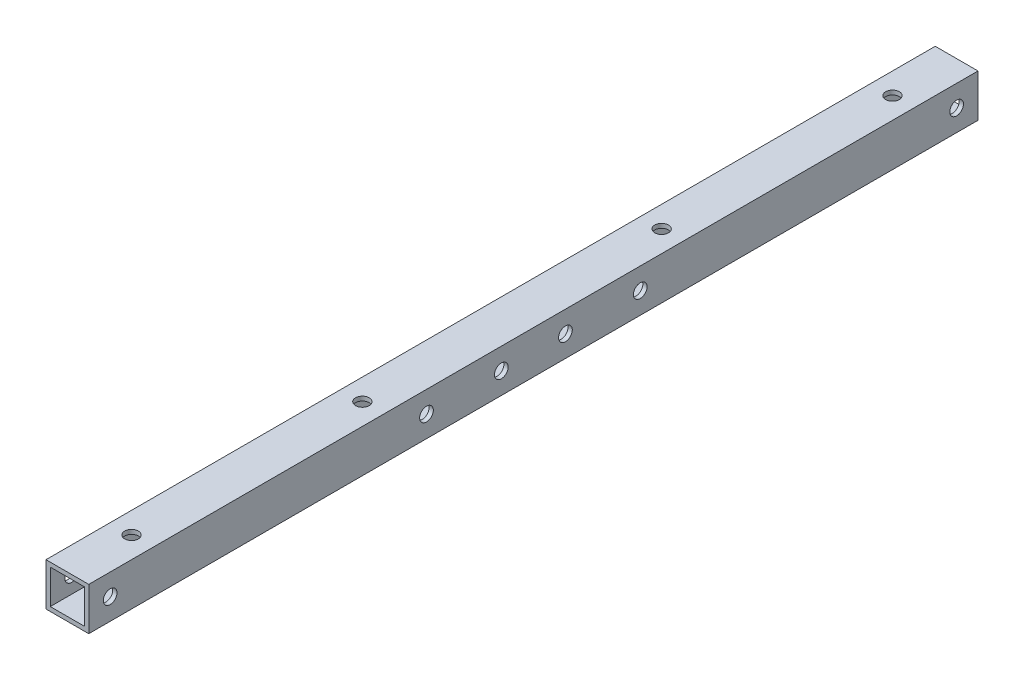
SolidWorks part; units mm, degrees
ref_plane "正面" through (0, 0, 0) normal (0, 0, 1) x (1, 0, 0)
ref_plane "平面" through (0, 0, 0) normal (0, 1, 0) x (1, 0, 0)
ref_plane "右側面" through (0, 0, 0) normal (1, 0, 0) x (0, 0, -1)
sketch "ｽｹｯﾁ1" plane through (0, 0, 0) normal (0, 0, 1) x (1, 0, 0)
  line L0 (-4, 4) -> (-4, -4)
  line L1 (-5, 5) -> (5, 5)
  line L2 (-5, 5) -> (-5, -5)
  line L3 (-5, -5) -> (5, -5)
  line L4 (5, 5) -> (5, -5)
  line L5 (-5, 5) -> (5, -5) construction
  line L6 (-5, -5) -> (5, 5) construction
  line L7 (-4, -4) -> (4, -4)
  line L8 (4, 4) -> (4, -4)
  line L9 (-4, 4) -> (4, 4)
  point P0 (0, 0)
  dimension "D1" = 10
  dimension "D2" = 10
  dimension "D3" = 1
extrude "ﾎﾞｽ - 押し出し1" add sketch "ｽｹｯﾁ1" along normal blind 208
sketch "ｽｹｯﾁ2" plane through (5, 0, 0) normal (1, 0, 0) x (0, 0, -1)
  line L0 (5.5, 0) -> (-5.5, 0) construction
  line L1 (-208, -5) -> (-208, 5) construction
  line L2 (0, 5.5) -> (0, -5.5) construction
  circle A0 centre (-203, 0) radius 1.6
  circle A1 centre (-111.5, 0) radius 1.6
  circle A2 centre (-96.5, 0) radius 1.6
  circle A3 centre (-5, 0) radius 1.6
  dimension "D1" = 3.2
  dimension "D2" = 3.2
  dimension "D3" = 3.2
  dimension "D4" = 3.2
  dimension "D5" = 5
  dimension "D6" = 5
  dimension "D7" = 15
  dimension "D8" = 96.5
extrude "ｶｯﾄ - 押し出し1" cut sketch "ｽｹｯﾁ2" against normal through all
sketch "ｽｹｯﾁ3" plane through (0, 5, 0) normal (0, 1, 0) x (1, 0, 0)
  line L0 (0, -5.5) -> (0, 5.5) construction
  line L1 (5, -208) -> (-5, -208) construction
  line L2 (-5.5, 0) -> (5.5, 0) construction
  circle A0 centre (0, -193) radius 1.6
  circle A1 centre (0, -15) radius 1.6
  dimension "D1" = 3.2
  dimension "D2" = 15
  dimension "D3" = 3.2
  dimension "D4" = 15
extrude "ｶｯﾄ - 押し出し2" cut sketch "ｽｹｯﾁ3" against normal through all
sketch "ｽｹｯﾁ4" plane through (5, 0, 0) normal (1, 0, 0) x (0, 0, -1)
  line L0 (5.5, 0) -> (-5.5, 0) construction
  line L1 (-208, -5) -> (-208, 5) construction
  circle A0 centre (-129, 0) radius 1.6
  circle A1 centre (-79, 0) radius 1.6
  dimension "D1" = 3.2
  dimension "D2" = 3.2
  dimension "D3" = 50
  dimension "D4" = 79
extrude "ｶｯﾄ - 押し出し3" cut sketch "ｽｹｯﾁ4" against normal through all
sketch "ｽｹｯﾁ5" plane through (0, 5, 0) normal (0, 1, 0) x (1, 0, 0)
  line L0 (0, -5.5) -> (0, 5.5) construction
  line L1 (5, -208) -> (-5, -208) construction
  line L2 (-5.5, 0) -> (5.5, 0) construction
  circle A0 centre (0, -139) radius 1.6
  circle A1 centre (0, -69) radius 1.6
  dimension "D1" = 3.2
  dimension "D2" = 3.2
  dimension "D3" = 69
  dimension "D4" = 69
extrude "ｶｯﾄ - 押し出し4" cut sketch "ｽｹｯﾁ5" against normal through all
equation "\"D8@ｽｹｯﾁ2\"=104-7.5"
